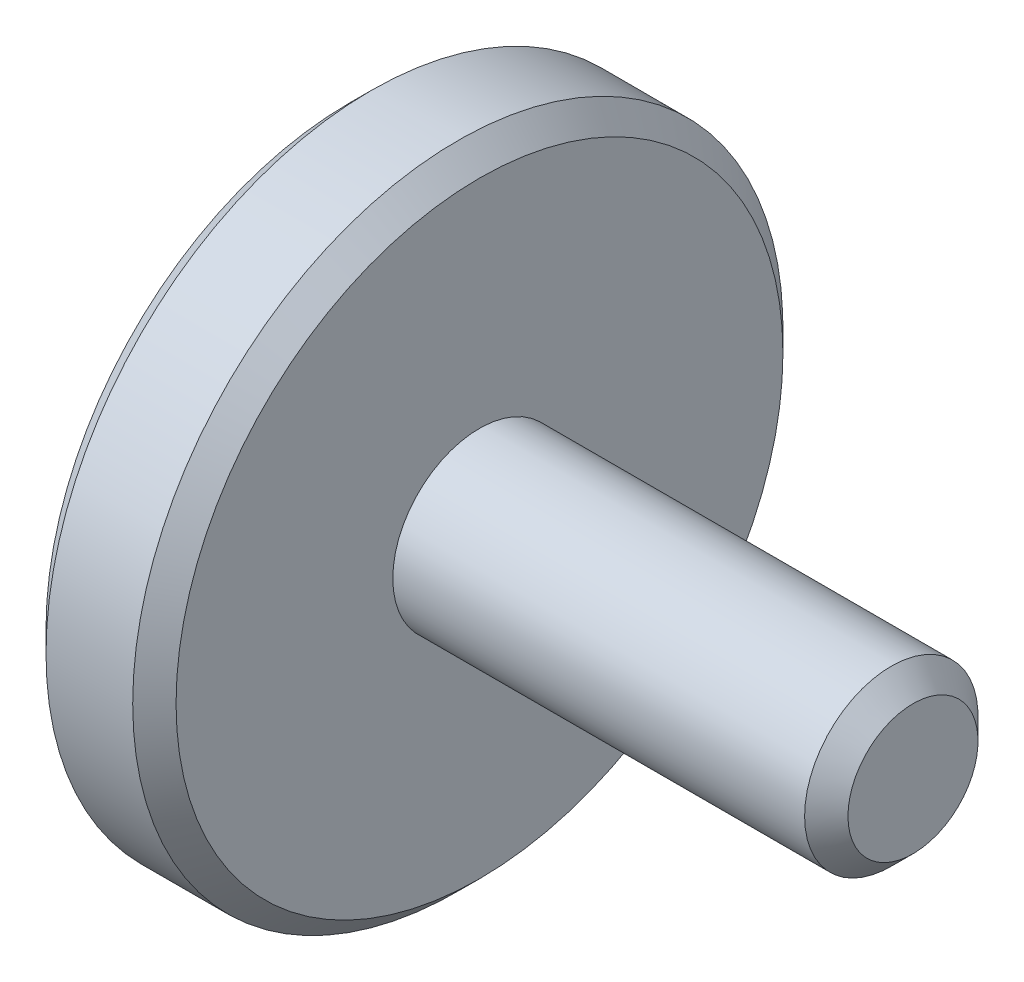
SolidWorks part; units mm, degrees
ref_plane "Plan de face" through (0, 0, 0) normal (0, 0, 1) x (1, 0, 0)
ref_plane "Plan de dessus" through (0, 0, 0) normal (0, 1, 0) x (1, 0, 0)
ref_plane "Plan de droite" through (0, 0, 0) normal (1, 0, 0) x (0, 0, -1)
sketch "Esquisse1" plane through (0, 0, 0) normal (0, 0, 1) x (1, 0, 0)
  line L0 (0, 0) -> (0, 7.5)
  line L1 (0, 7.5) -> (3, 7.5)
  line L2 (3, 7.5) -> (3, 2)
  line L3 (3, 2) -> (13, 2)
  line L4 (13, 2) -> (13, 0)
  line L5 (13, 0) -> (0, 0)
  line L6 (-65.1704, 0) -> (117.1561, 0) construction
  dimension "D1" = 4
  dimension "D2" = 10
  dimension "D3" = 3
  dimension "D4" = 15
revolve "Révolution1" add sketch "Esquisse1" angle 360 about L6
cosmetic thread "Représentation de filetage1" parameters "D2"=3.3
chamfer "Chanfrein1" distance 0.5 angle 45 3 edges at (0, 0, 7.5) (3, 0, 7.5) (13, 0, 2)
